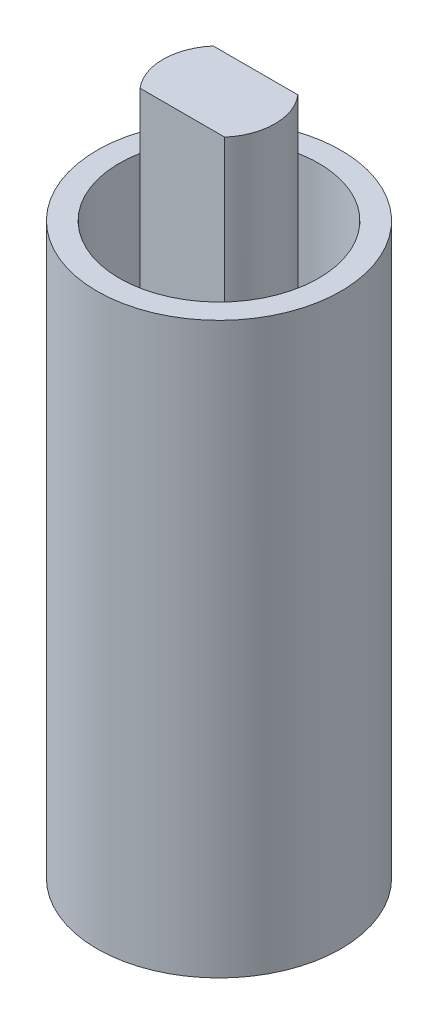
SolidWorks part; units mm, degrees
ref_plane "Front Plane" through (0, 0, 0) normal (0, 0, 1) x (1, 0, 0)
ref_plane "Top Plane" through (0, 0, 0) normal (0, 1, 0) x (1, 0, 0)
ref_plane "Right Plane" through (0, 0, 0) normal (1, 0, 0) x (0, 0, -1)
sketch "Sketch1" plane through (0, 0, 0) normal (0, 1, 0) x (1, 0, 0)
  circle A0 centre (0, 0) radius 2.75
  dimension "D1" = 5.5
extrude "Boss-Extrude1" add sketch "Sketch1" along normal blind 1.8
sketch "Sketch3" plane through (0, 1.8, 0) normal (0, 1, 0) x (1, 0, 0)
  line L0 (-2.0791, 1.8) -> (2.0791, 1.8)
  line L1 (-2.0791, -1.8) -> (2.0791, -1.8)
  arc A0 (-2.0791, 1.8) -> (-2.0791, -1.8) centre (0, 0) ccw
  arc A2 (2.0791, -1.8) -> (2.0791, 1.8) centre (0, 0) ccw
  dimension "D1" = 4.1581
extrude "Boss-Extrude2" add sketch "Sketch3" along normal blind 21.7
sketch "Sketch4" plane through (0, 0, 0) normal (0, -1, 0) x (1, 0, 0)
  circle A0 centre (0, 0) radius 6
  dimension "D1" = 12
extrude "Boss-Extrude3" add sketch "Sketch4" along normal blind 10
sketch "Sketch5" plane through (0, 0, 0) normal (0, 1, 0) x (1, 0, 0)
  circle A0 centre (0, 0) radius 4.9
  circle A1 centre (0, 0) radius 6
  circle A2 centre (0, 0) radius 6 construction
  dimension "D1" = 9.8
extrude "Boss-Extrude4" add sketch "Sketch5" along normal blind 18
